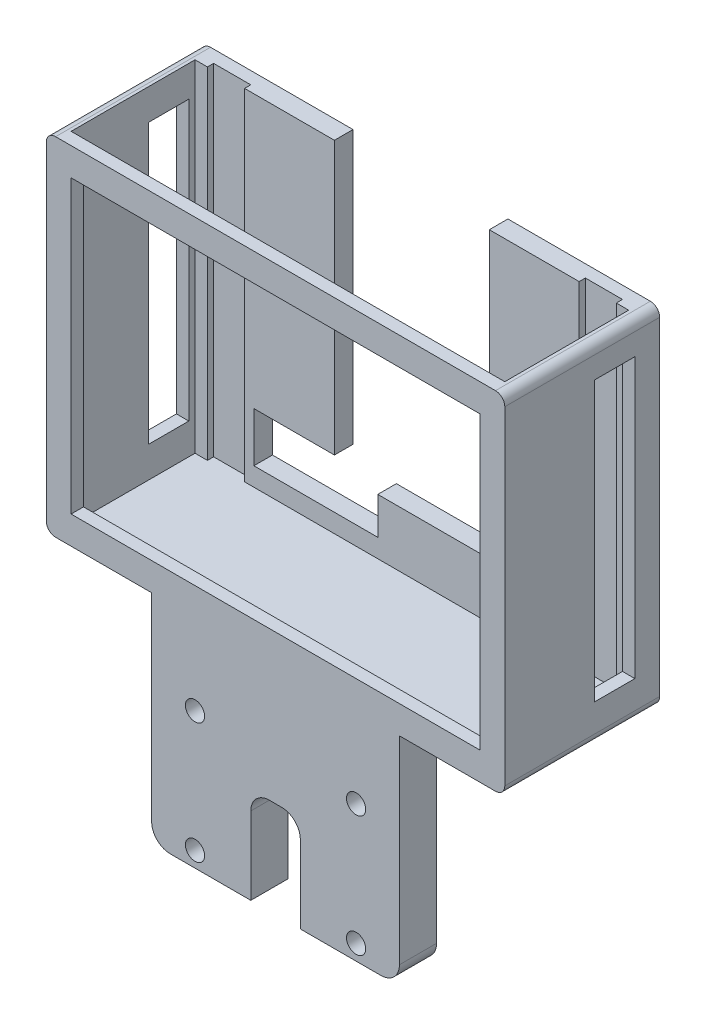
SolidWorks part; units mm, degrees
ref_plane "前视基准面" through (0, 0, 0) normal (0, 0, 1) x (1, 0, 0)
ref_plane "上视基准面" through (0, 0, 0) normal (0, 1, 0) x (1, 0, 0)
ref_plane "右视基准面" through (0, 0, 0) normal (1, 0, 0) x (0, 0, -1)
sketch "草图1" plane through (0, 0, 0) normal (0, 0, 1) x (1, 0, 0)
  line L1 (-40, -30) -> (40, -30)
  line L2 (-40, -30) -> (-40, 30)
  line L3 (-40, 30) -> (40, 30)
  line L4 (40, -30) -> (40, 30)
  line L5 (-40, -30) -> (40, 30) construction
  line L6 (-40, 30) -> (40, -30) construction
  point P0 (0, 0)
  dimension "D1" = 80
  dimension "D2" = 60
extrude "凸台-拉伸1" add sketch "草图1" along normal blind 3
sketch "草图2" plane through (0, 0, 3) normal (0, 0, 1) x (1, 0, 0)
  line L0 (40, 30) -> (-40, 30) construction
  line L2 (-12.5, -8.5) -> (-12.5, 8.5)
  line L4 (12.5, -8.5) -> (12.5, 8.5)
  line L5 (-12.5, -8.5) -> (12.5, 8.5) construction
  line L6 (-12.5, 8.5) -> (12.5, -8.5) construction
  line L8 (-12.5, -8.5) -> (-12.5, -16)
  line L9 (-12.5, -16) -> (12.5, -16)
  line L10 (12.5, -8.5) -> (12.5, -16)
  line L12 (-12.5, 8.5) -> (-12.5, 30)
  line L13 (-12.5, 30) -> (12.5, 30)
  line L14 (12.5, 8.5) -> (12.5, 30)
  point P0 (0, 0)
  dimension "D1" = 25
  dimension "D2" = 17
  dimension "D3" = 7.5
extrude "切除-拉伸1" cut sketch "草图2" against normal blind 3
sketch "草图3" plane through (0, 0, 3) normal (0, 0, 1) x (1, 0, 0)
  line L0 (-40, 30) -> (-35, 30)
  line L1 (-40, 30) -> (40, 30) construction
  line L2 (-40, 30) -> (-40, -30) construction
  line L3 (-40, -30) -> (40, -30) construction
  line L4 (40, 30) -> (40, -30) construction
  line L5 (-35, 30) -> (-35, -25)
  line L6 (-35, -25) -> (35, -25)
  line L7 (35, -25) -> (35, 30)
  line L8 (35, 30) -> (40, 30)
  line L9 (40, 30) -> (40, -30)
  line L10 (40, -30) -> (-40, -30)
  line L11 (-40, -30) -> (-40, 30)
  dimension "D1" = 5
  dimension "D2" = 5
  dimension "D3" = 5
extrude "凸台-拉伸2" add sketch "草图3" along normal blind 20
sketch "草图4" plane through (-40, 0, 0) normal (-1, 0, 0) x (0, 0, 1)
  line L0 (23, -30) -> (0, -30) construction
  line L1 (0, 30) -> (3, 30) construction
  line L2 (0, 30) -> (0, -30) construction
  line L3 (0, -30) -> (3, -30) construction
  line L4 (3, 30) -> (3, -30) construction
  line L5 (23, 30) -> (0, 30) construction
  line L6 (3, 25) -> (4, 25) construction
  line L7 (3, 25) -> (3, -20) construction
  line L8 (3, -20) -> (4, -20) construction
  line L9 (4, 25) -> (4, -20) construction
  line L11 (4, 25) -> (10.5, 25)
  line L12 (4, 25) -> (4, -20)
  line L13 (4, -20) -> (10.5, -20)
  line L14 (10.5, 25) -> (10.5, -20)
  dimension "D1" = 3
  dimension "D2" = 10
  dimension "D3" = 5
  dimension "D4" = 6.5
  dimension "D5" = 1
extrude "切除-拉伸2" cut sketch "草图4" against normal through all
sketch "草图5" plane through (0, 0, 3) normal (0, 0, 1) x (1, 0, 0)
  line L1 (-35, -25) -> (-35, 30) construction
  line L2 (0, 0) -> (0, -66.8849) construction
  line L3 (-12.5, 30) -> (-35, 30) construction
  line L5 (35, -25) -> (-35, -25) construction
  line L6 (-33, 30) -> (-27, 30)
  line L7 (-33, 30) -> (-33, -25)
  line L8 (-33, -25) -> (-27, -25)
  line L9 (-27, 30) -> (-27, -25)
  line L10 (33, -25) -> (27, -25)
  line L11 (33, 30) -> (33, -25)
  line L12 (33, 30) -> (27, 30)
  line L13 (27, 30) -> (27, -25)
  point P12 (-30, 26.5)
  dimension "D3" = 3.5
  dimension "D4" = 2
  dimension "D1" = 6
extrude "切除-拉伸3" cut sketch "草图5" against normal blind 1
sketch "草图7" plane through (0, 0, 3) normal (0, 0, 1) x (1, 0, 0)
  line L0 (35, -25) -> (-35, -25) construction
  line L1 (-25.5, -22) -> (-5.5, -22)
  line L2 (-25.5, -22) -> (-25.5, -14)
  line L3 (-25.5, -14) -> (-5.5, -14)
  line L4 (-5.5, -22) -> (-5.5, -14)
  line L5 (-35, -25) -> (-35, 30) construction
  line L6 (27, -25) -> (-27, -25) construction
  line L7 (25.5, -22) -> (25.5, -14)
  line L8 (25.5, -22) -> (13.5, -22)
  line L9 (13.5, -22) -> (13.5, -14)
  line L10 (25.5, -14) -> (13.5, -14)
  line L11 (35, 30) -> (35, -25) construction
  dimension "D1" = 3
  dimension "D2" = 9.5
  dimension "D3" = 20
  dimension "D4" = 8
  dimension "D5" = 12
  dimension "D6" = 8
  dimension "D7" = 3
  dimension "D8" = 9.5
extrude "切除-拉伸4" cut sketch "草图7" against normal blind 3
sketch "草图8" plane through (0, 0, 23) normal (0, 0, 1) x (1, 0, 0)
  line L0 (-40, 30) -> (-32, 30)
  line L1 (-12.5, 30) -> (-27, 30) construction
  line L2 (-33, 25.5) -> (-33, -21.5)
  line L3 (-33, -21.5) -> (33, -21.5)
  line L4 (33, -21.5) -> (33, 25.5)
  line L5 (35, 30) -> (33, 30) construction
  line L6 (32, 30) -> (40, 30)
  line L7 (40, 30) -> (40, -30)
  line L8 (40, -30) -> (-40, -30)
  line L9 (-40, -30) -> (-40, 30)
  line L11 (-32, 30) -> (32, 30)
  line L13 (-33, 25.5) -> (33, 25.5)
  dimension "D1" = 8
  dimension "D2" = 8
  dimension "D3" = 8.5
  dimension "D4" = 4.5
extrude "凸台-拉伸3" add sketch "草图8" along normal blind 2
sketch "草图9" plane through (0, 0, 25) normal (0, 0, 1) x (1, 0, 0)
  line L1 (-40, 30) -> (40, 30) construction
  line L2 (-40, 30) -> (-40, -30) construction
  line L3 (-40, -30) -> (40, -30) construction
  line L4 (40, 30) -> (40, -30) construction
  line L5 (-40, 30) -> (-37, 30)
  line L6 (-40, 30) -> (-40, -30)
  line L7 (-40, -30) -> (-38, -30)
  line L8 (-37, 30) -> (-37, -26)
  line L9 (40, 30) -> (37, 30)
  line L10 (40, 30) -> (40, -30)
  line L11 (40, -30) -> (38, -30)
  line L12 (37, 30) -> (37, -26)
  line L13 (-37, -26) -> (37, -26)
  line L15 (-38, -30) -> (38, -30)
  dimension "D1" = 3
  dimension "D2" = 3
  dimension "D3" = 4
extrude "切除-拉伸5" cut sketch "草图9" against normal through all
sketch "草图11" plane through (0, 0, 25) normal (0, 0, 1) x (1, 0, 0)
  line L12 (-35.5, 30) -> (-37, 30)
  line L17 (-37, 30) -> (-37, 28.5)
  line L18 (-37, -24.5) -> (-37, -26)
  line L19 (-37, -26) -> (-35.5, -26)
  line L20 (37, -24.5) -> (37, -26)
  line L21 (37, -26) -> (35.5, -26)
  line L22 (35.5, 30) -> (37, 30)
  line L23 (37, 30) -> (37, 28.5)
  arc A4 (-37, -24.5) -> (-35.5, -26) centre (-35.5, -24.5) ccw
  arc A5 (35.5, -26) -> (37, -24.5) centre (35.5, -24.5) ccw
  arc A6 (35.5, 30) -> (37, 28.5) centre (35.5, 28.5) cw
  arc A7 (-35.5, 30) -> (-37, 28.5) centre (-35.5, 28.5) ccw
  point P10 (37, -26)
  point P13 (37, -26)
  point P16 (-37, 30)
  dimension "D1" = 1.5
extrude "切除-拉伸6" cut sketch "草图11" against normal through all
sketch "草图12" plane through (0, -26, 0) normal (0, -1, 0) x (1, 0, 0)
  line L0 (35.5, 0) -> (-35.5, 0) construction
  line L1 (-20, 19) -> (20, 19)
  line L2 (-20, 19) -> (-20, 25)
  line L3 (-20, 25) -> (20, 25)
  line L4 (20, 19) -> (20, 25)
  line L5 (35.5, 25) -> (-35.5, 25) construction
  point P6 (0, 0)
  dimension "D1" = 40
  dimension "D2" = 20
  dimension "D3" = 6
extrude "凸台-拉伸4" add sketch "草图12" along normal blind 35
sketch "草图13" plane through (0, 0, 25) normal (0, 0, 1) x (1, 0, 0)
  line L0 (-4, -61) -> (4, -61)
  line L5 (-33, -21.5) -> (33, -21.5) construction
  line L10 (20, -58) -> (20, -61)
  line L18 (-13, -58.5) -> (13, -58.5) construction
  line L20 (-13, -39) -> (13, -39) construction
  line L22 (20, -61) -> (17, -61)
  line L24 (20, -61) -> (-20, -61) construction
  line L25 (0, -45.5) -> (1, -45.5)
  line L28 (4, -48.5) -> (4, -61)
  line L29 (-20, -58) -> (-20, -61)
  line L32 (0, -45.5) -> (-1, -45.5)
  line L33 (-4, -61) -> (-4, -48.5)
  line L35 (-20, -61) -> (-17, -61)
  circle A0 centre (-13, -39) radius 1.55
  circle A1 centre (13, -39) radius 1.55
  circle A2 centre (-13, -58.5) radius 1.55
  circle A3 centre (13, -58.5) radius 1.55
  arc A4 (-1, -45.5) -> (-4, -48.5) centre (-1, -48.5) ccw
  arc A5 (1, -45.5) -> (4, -48.5) centre (1, -48.5) cw
  arc A7 (-20, -58) -> (-17, -61) centre (-17, -58) ccw
  arc A8 (20, -58) -> (17, -61) centre (17, -58) cw
  point P0 (0, -45.5)
  point P8 (0, -45.5)
  point P9 (0, -45.5)
  point P12 (20, -61)
  point P23 (0, -21.5)
  point P47 (-20, -61)
  dimension "D6" = 8
  dimension "D8" = 3
  dimension "D1" = 3
  dimension "D2" = 19.5
  dimension "D3" = 15.5
  dimension "D5" = 26
  dimension "D7" = 4
extrude "切除-拉伸7" cut sketch "草图13" against normal through all
